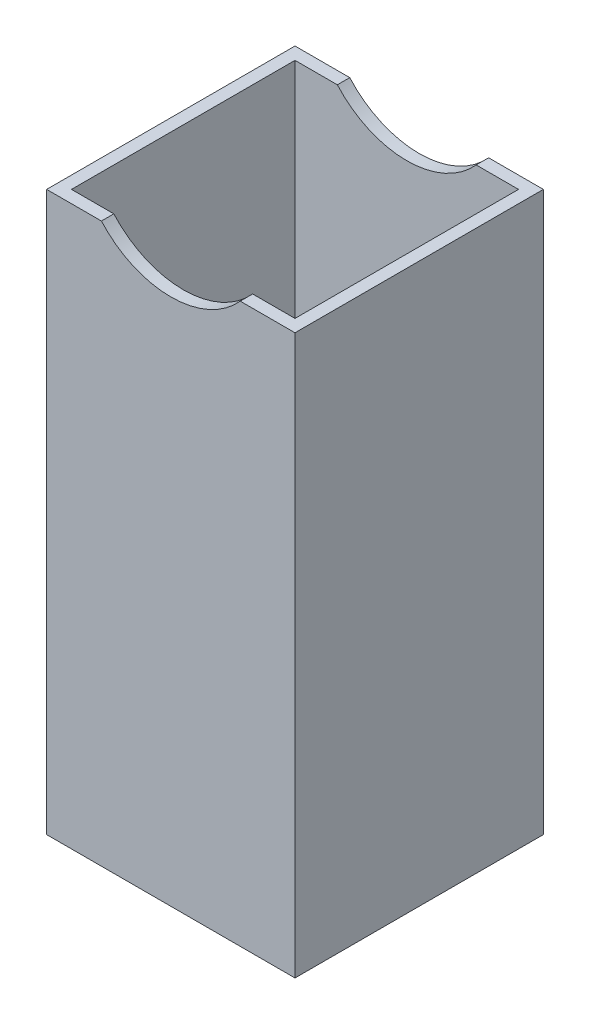
SolidWorks part; units mm, degrees
ref_plane "Plano frontal" through (0, 0, 0) normal (0, 0, 1) x (1, 0, 0)
ref_plane "Plano superior" through (0, 0, 0) normal (0, 1, 0) x (1, 0, 0)
ref_plane "Plano direito" through (0, 0, 0) normal (1, 0, 0) x (0, 0, -1)
sketch "Esboço1" plane through (0, 0, 0) normal (0, 1, 0) x (1, 0, 0)
  line L0 (-18, 18) -> (18, 18)
  line L1 (-20, -20) -> (20, -20)
  line L2 (-20, -20) -> (-20, 20)
  line L3 (-20, 20) -> (20, 20)
  line L4 (20, -20) -> (20, 20)
  line L5 (-20, -20) -> (20, 20) construction
  line L6 (-20, 20) -> (20, -20) construction
  line L7 (18, -18) -> (18, 18)
  line L8 (-18, -18) -> (18, -18)
  line L9 (-18, -18) -> (-18, 18)
  point P0 (0, 0)
  dimension "D1" = 40
  dimension "D2" = 40
  dimension "D3" = 2
sketch "Esboço2" plane through (0, 0, 0) normal (1, 0, 0) x (0, 0, -1)
  line L0 (0, 0) -> (0, -90)
  dimension "D1" = 90
sweep "Varredura1" add profiles "Esboço1" path "Esboço2"
sketch "Esboço3" plane through (0, 0, 20) normal (0, 0, 1) x (1, 0, 0)
  circle A0 centre (0, 10) radius 15
  dimension "D1" = 30
  dimension "D2" = 10
extrude "Corte-extrusão1" cut sketch "Esboço3" against normal blind 50
